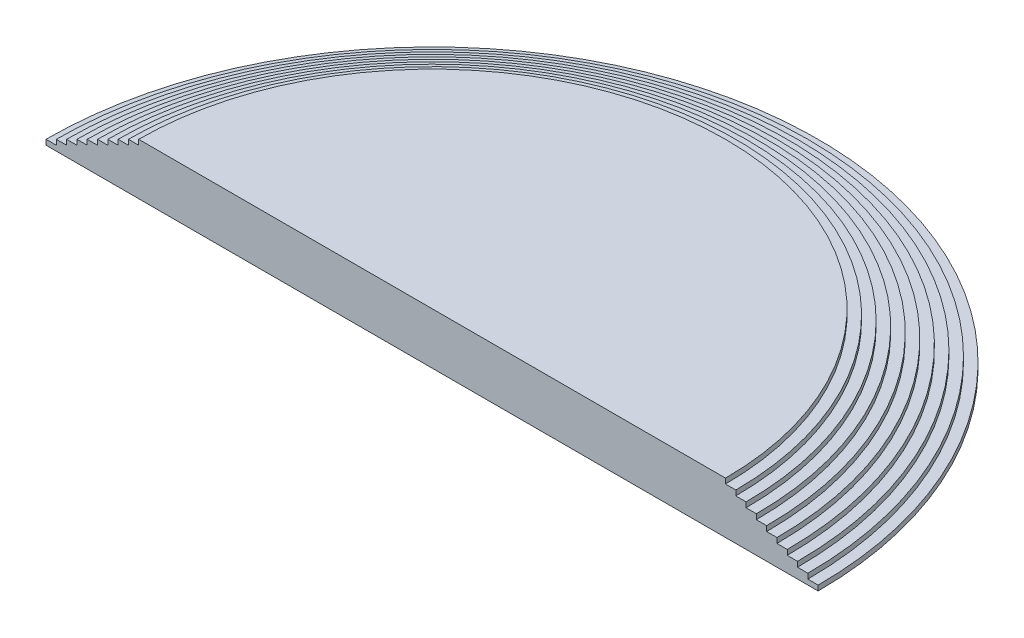
SolidWorks part; units mm, degrees
ref_plane "前视基准面" through (0, 0, 0) normal (0, 0, 1) x (1, 0, 0)
ref_plane "上视基准面" through (0, 0, 0) normal (0, 1, 0) x (1, 0, 0)
ref_plane "右视基准面" through (0, 0, 0) normal (1, 0, 0) x (0, 0, -1)
sketch "草图1" plane through (0, 0, 0) normal (0, 1, 0) x (1, 0, 0)
  line L0 (-43.9571, 0) -> (41.6282, 0) construction
  line L1 (-15, 0) -> (15, 0)
  arc A0 (15, 0) -> (-15, 0) centre (0, 0) ccw
  dimension "D1" = 30
extrude "凸台-拉伸1" add sketch "草图1" along normal blind 0.2
sketch "草图2" plane through (0, 0.2, 0) normal (0, 1, 0) x (1, 0, 0)
  line L0 (-15, 0) -> (15, 0) construction
  line L1 (-14.6, 0) -> (14.6, 0)
  arc A0 (15, 0) -> (-15, 0) centre (0, 0) ccw construction
  arc A1 (15, 0) -> (-15, 0) centre (0, 0) ccw construction
  arc A2 (14.6, 0) -> (-14.6, 0) centre (0, 0) ccw
  dimension "D1" = 0.4
extrude "凸台-拉伸3" add sketch "草图2" along normal blind 0.2
sketch "草图3" plane through (0, 0.4, 0) normal (0, 1, 0) x (1, 0, 0)
  line L0 (-14.2, 0) -> (14.2, 0)
  arc A0 (14.6, 0) -> (-14.6, 0) centre (0, 0) ccw construction
  arc A1 (14.6, 0) -> (-14.6, 0) centre (0, 0) ccw construction
  arc A2 (14.2, 0) -> (-14.2, 0) centre (0, 0) ccw
  dimension "D1" = 0.4
extrude "凸台-拉伸4" add sketch "草图3" along normal blind 0.2
sketch "草图4" plane through (0, 0.6, 0) normal (0, 1, 0) x (1, 0, 0)
  line L0 (-13.8, 0) -> (13.8, 0)
  arc A0 (14.2, 0) -> (-14.2, 0) centre (0, 0) ccw construction
  arc A1 (14.2, 0) -> (-14.2, 0) centre (0, 0) ccw construction
  arc A2 (13.8, 0) -> (-13.8, 0) centre (0, 0) ccw
  dimension "D1" = 0.4
extrude "凸台-拉伸5" add sketch "草图4" along normal blind 0.2
sketch "草图5" plane through (0, 0.8, 0) normal (0, 1, 0) x (1, 0, 0)
  line L1 (-13.4, 0) -> (13.4, 0)
  arc A0 (13.8, 0) -> (-13.8, 0) centre (0, 0) ccw construction
  arc A1 (13.8, 0) -> (-13.8, 0) centre (0, 0) ccw construction
  arc A3 (13.4, 0) -> (-13.4, 0) centre (0, 0) ccw
  dimension "D1" = 0.4
extrude "凸台-拉伸6" add sketch "草图5" along normal blind 0.2 contours A3 L1
sketch "草图6" plane through (0, 1, 0) normal (0, 1, 0) x (1, 0, 0)
  line L1 (-13, 0) -> (13, 0)
  arc A0 (13.4, 0) -> (-13.4, 0) centre (0, 0) ccw construction
  arc A1 (13.4, 0) -> (-13.4, 0) centre (0, 0) ccw construction
  arc A3 (13, 0) -> (-13, 0) centre (0, 0) ccw
  dimension "D1" = 0.4
extrude "凸台-拉伸7" add sketch "草图6" along normal blind 0.2
sketch "草图7" plane through (0, 1.2, 0) normal (0, 1, 0) x (1, 0, 0)
  line L0 (-12.6, 0) -> (12.6, 0)
  arc A0 (13, 0) -> (-13, 0) centre (0, 0) ccw construction
  arc A1 (13, 0) -> (-13, 0) centre (0, 0) ccw construction
  arc A2 (12.6, 0) -> (-12.6, 0) centre (0, 0) ccw
  dimension "D1" = 0.4
extrude "凸台-拉伸8" add sketch "草图7" along normal blind 0.2
sketch "草图8" plane through (0, 1.4, 0) normal (0, 1, 0) x (1, 0, 0)
  line L0 (-12.2, 0) -> (12.2, 0)
  arc A0 (12.6, 0) -> (-12.6, 0) centre (0, 0) ccw construction
  arc A1 (12.6, 0) -> (-12.6, 0) centre (0, 0) ccw construction
  arc A2 (12.2, 0) -> (-12.2, 0) centre (0, 0) ccw
  dimension "D1" = 0.4
extrude "凸台-拉伸9" add sketch "草图8" along normal blind 0.2
sketch "草图9" plane through (0, 1.6, 0) normal (0, 1, 0) x (1, 0, 0)
  line L0 (-11.8, 0) -> (11.8, 0)
  arc A0 (12.2, 0) -> (-12.2, 0) centre (0, 0) ccw construction
  arc A1 (12.2, 0) -> (-12.2, 0) centre (0, 0) ccw construction
  arc A2 (11.8, 0) -> (-11.8, 0) centre (0, 0) ccw
  dimension "D1" = 0.4
extrude "凸台-拉伸10" add sketch "草图9" along normal blind 0.2
sketch "草图10" plane through (0, 1.8, 0) normal (0, 1, 0) x (1, 0, 0)
  line L0 (-11.4, 0) -> (11.4, 0)
  arc A0 (11.8, 0) -> (-11.8, 0) centre (0, 0) ccw construction
  arc A1 (11.8, 0) -> (-11.8, 0) centre (0, 0) ccw construction
  arc A2 (11.4, 0) -> (-11.4, 0) centre (0, 0) ccw
  dimension "D1" = 0.4
extrude "凸台-拉伸11" add sketch "草图10" along normal blind 0.2
